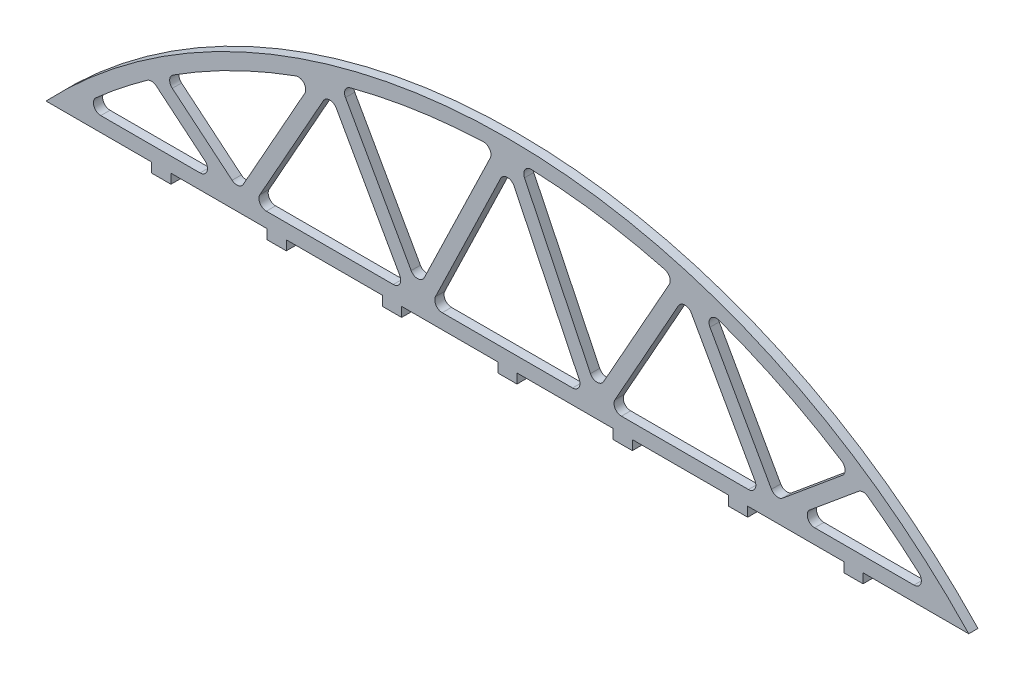
SolidWorks part; units mm, degrees
ref_plane "Front Plane" through (0, 0, 0) normal (0, 0, 1) x (1, 0, 0)
ref_plane "Top Plane" through (0, 0, 0) normal (0, 1, 0) x (1, 0, 0)
ref_plane "Right Plane" through (0, 0, 0) normal (1, 0, 0) x (0, 0, -1)
sketch "Sketch1" plane through (0, 0, 0) normal (0, 0, 1) x (1, 0, 0)
  line L0 (163.6551, -60.2333) -> (11.2551, 92.1667) construction
  line L1 (11.2551, -60.2333) -> (11.2551, -2.9488) construction
  line L2 (50.4102, -57.6933) -> (94.0199, -57.6933)
  line L3 (-147.1584, -62.7733) -> (169.6685, -62.7733)
  line L4 (105.7637, -54.3809) -> (126.2967, -37.319)
  line L5 (80.8174, -16.049) -> (101.9253, -53.6702)
  line L6 (44.2879, -50.4923) -> (66.8338, -10.3082)
  line L7 (-21.7778, -50.4923) -> (-44.3236, -10.3082)
  line L8 (-58.3072, -16.049) -> (-79.4151, -53.6702)
  line L9 (-83.2536, -54.3809) -> (-103.7865, -37.319)
  line L10 (-128.343, -57.6933) -> (-94.247, -57.6933)
  line L11 (74.4302, -15.047) -> (96.2351, -53.9104)
  line L12 (48.1951, -53.9104) -> (69.9999, -15.047)
  line L13 (13.5424, -7.686) -> (35.9284, -54.0489)
  line L14 (8.9678, -7.686) -> (-13.4182, -54.0489)
  line L15 (-25.6849, -53.9104) -> (-47.4898, -15.047)
  line L16 (-51.9201, -15.047) -> (-73.7249, -53.9104)
  line L17 (17.1384, -3.4502) -> (39.7855, -50.3538)
  line L18 (11.2551, 2.8929) -> (11.2551, 92.1667) construction
  line L19 (5.3718, -3.4502) -> (-17.2753, -50.3538)
  line L20 (115.1339, -53.1997) -> (131.8169, -39.3369)
  line L21 (-11.1309, -57.6933) -> (33.6411, -57.6933)
  line L22 (-71.5098, -57.6933) -> (-27.9001, -57.6933)
  line L23 (116.7572, -57.6933) -> (150.8532, -57.6933)
  line L24 (-92.6237, -53.1997) -> (-109.3068, -39.3369)
  arc A0 (-147.1584, -62.7733) -> (169.6685, -62.7733) centre (11.2551, -212.6333) cw
  arc A1 (-130.0279, -53.2526) -> (-112.4048, -39.2224) centre (11.2551, -212.6333) cw
  arc A2 (17.1384, -3.4502) -> (19.5243, 0.1923) centre (19.4257, -2.3458) cw
  arc A3 (134.915, -39.2224) -> (152.5381, -53.2526) centre (11.2551, -212.6333) cw
  arc A4 (83.8989, -12.4184) -> (126.0423, -33.2259) centre (11.2551, -212.6333) cw
  arc A5 (65.2627, -6.6083) -> (66.8338, -10.3082) centre (64.6186, -9.0653) cw
  arc A6 (19.5243, 0.1923) -> (65.2627, -6.6083) centre (11.2551, -212.6333) cw
  arc A7 (-42.7525, -6.6083) -> (2.9858, 0.1923) centre (11.2551, -212.6333) cw
  arc A8 (-103.5321, -33.2259) -> (-61.3887, -12.4184) centre (11.2551, -212.6333) cw
  arc A9 (44.2879, -50.4923) -> (39.7855, -50.3538) centre (42.0728, -49.2494) cw
  arc A10 (48.1951, -53.9104) -> (50.4102, -57.6933) centre (50.4102, -55.1533) ccw
  arc A11 (94.0199, -57.6933) -> (96.2351, -53.9104) centre (94.0199, -55.1533) ccw
  arc A12 (74.4302, -15.047) -> (69.9999, -15.047) centre (72.2151, -16.2898) ccw
  arc A13 (83.8989, -12.4184) -> (80.8174, -16.049) centre (83.0325, -14.8061) ccw
  arc A14 (126.0423, -33.2259) -> (126.2967, -37.319) centre (124.6733, -35.3655) cw
  arc A15 (105.7637, -54.3809) -> (101.9253, -53.6702) centre (104.1404, -52.4273) cw
  arc A16 (115.1339, -53.1997) -> (116.7572, -57.6933) centre (116.7572, -55.1533) ccw
  arc A17 (134.915, -39.2224) -> (131.8169, -39.3369) centre (133.4403, -41.2905) ccw
  arc A18 (152.5381, -53.2526) -> (150.8532, -57.6933) centre (150.8532, -55.1533) cw
  arc A19 (13.5424, -7.686) -> (8.9678, -7.686) centre (11.2551, -8.7904) ccw
  arc A20 (35.9284, -54.0489) -> (33.6411, -57.6933) centre (33.6411, -55.1533) cw
  arc A21 (-11.1309, -57.6933) -> (-13.4182, -54.0489) centre (-11.1309, -55.1533) cw
  arc A22 (-17.2753, -50.3538) -> (-21.7778, -50.4923) centre (-19.5626, -49.2494) cw
  arc A23 (5.3718, -3.4502) -> (2.9858, 0.1923) centre (3.0845, -2.3458) ccw
  arc A24 (-27.9001, -57.6933) -> (-25.6849, -53.9104) centre (-27.9001, -55.1533) ccw
  arc A25 (-130.0279, -53.2526) -> (-128.343, -57.6933) centre (-128.343, -55.1533) ccw
  arc A26 (-92.6237, -53.1997) -> (-94.247, -57.6933) centre (-94.247, -55.1533) cw
  arc A27 (-109.3068, -39.3369) -> (-112.4048, -39.2224) centre (-110.9301, -41.2905) ccw
  arc A28 (-103.7865, -37.319) -> (-103.5321, -33.2259) centre (-102.1632, -35.3655) cw
  arc A29 (-79.4151, -53.6702) -> (-83.2536, -54.3809) centre (-81.6302, -52.4273) cw
  arc A30 (-71.5098, -57.6933) -> (-73.7249, -53.9104) centre (-71.5098, -55.1533) cw
  arc A31 (-42.7525, -6.6083) -> (-44.3236, -10.3082) centre (-42.1084, -9.0653) ccw
  arc A32 (-47.4898, -15.047) -> (-51.9201, -15.047) centre (-49.7049, -16.2898) ccw
  arc A33 (-61.3887, -12.4184) -> (-58.3072, -16.049) centre (-60.5224, -14.8061) cw
  dimension "D1" = 2.54
extrude "Boss-Extrude1" add sketch "Sketch1" along normal blind 3.175
scale "Scale2" scale about centroid uniform scaling yes scale factor 0.962039
sketch "Sketch2" plane through (0, 0, 3.1147) normal (0, 0, 1) x (1, 0, 0)
  line L0 (-106.2199, -61.7826) -> (-99.8699, -61.7826)
  line L2 (-99.8699, -61.7826) -> (-99.8699, -64.9576)
  line L3 (-99.8699, -64.9576) -> (-106.2199, -64.9576)
  line L4 (-106.2199, -64.9576) -> (-106.2199, -61.7826)
  line L20 (-68.1199, -64.9576) -> (-68.1199, -61.7826)
  line L21 (-61.7699, -64.9576) -> (-68.1199, -64.9576)
  line L22 (-61.7699, -61.7826) -> (-61.7699, -64.9576)
  line L23 (-68.1199, -61.7826) -> (-61.7699, -61.7826)
  line L24 (-30.0199, -64.9576) -> (-30.0199, -61.7826)
  line L25 (-23.6699, -64.9576) -> (-30.0199, -64.9576)
  line L26 (-23.6699, -61.7826) -> (-23.6699, -64.9576)
  line L27 (-30.0199, -61.7826) -> (-23.6699, -61.7826)
  line L28 (8.0801, -64.9576) -> (8.0801, -61.7826)
  line L29 (14.4301, -64.9576) -> (8.0801, -64.9576)
  line L30 (14.4301, -61.7826) -> (14.4301, -64.9576)
  line L31 (8.0801, -61.7826) -> (14.4301, -61.7826)
  line L32 (46.1801, -64.9576) -> (46.1801, -61.7826)
  line L33 (52.5301, -64.9576) -> (46.1801, -64.9576)
  line L34 (52.5301, -61.7826) -> (52.5301, -64.9576)
  line L35 (46.1801, -61.7826) -> (52.5301, -61.7826)
  line L36 (84.2801, -64.9576) -> (84.2801, -61.7826)
  line L37 (90.6301, -64.9576) -> (84.2801, -64.9576)
  line L38 (90.6301, -61.7826) -> (90.6301, -64.9576)
  line L39 (84.2801, -61.7826) -> (90.6301, -61.7826)
  line L40 (122.3801, -64.9576) -> (122.3801, -61.7826)
  line L41 (128.7301, -64.9576) -> (122.3801, -64.9576)
  line L42 (128.7301, -61.7826) -> (128.7301, -64.9576)
  line L43 (122.3801, -61.7826) -> (128.7301, -61.7826)
  line L44 (-141.1449, -61.7826) -> (163.6551, -61.7826) construction
  line L45 (-141.1449, -61.7826) -> (-141.1449, -71.5793) construction
  dimension "D1" = 34.925
  dimension "D2" = 3.175
  dimension "D3" = 6.35
  dimension "D4" = 7
  dimension "D5" = 31.75
extrude "Boss-Extrude2" add sketch "Sketch2" against normal blind 3.175
